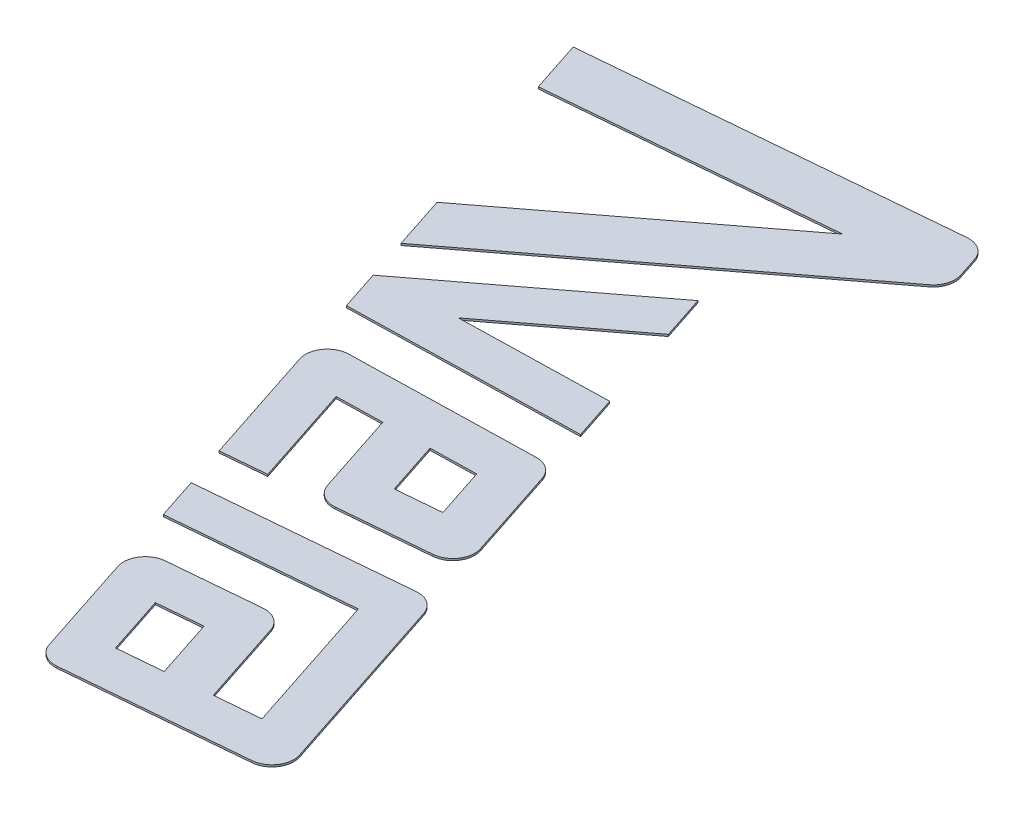
SolidWorks part; units mm, degrees
ref_plane "Front Plane" through (0, 0, 0) normal (0, 0, 1) x (1, 0, 0)
ref_plane "Top Plane" through (0, 0, 0) normal (0, 1, 0) x (1, 0, 0)
ref_plane "Right Plane" through (0, 0, 0) normal (1, 0, 0) x (0, 0, -1)
sketch "Sketch1" plane through (0, 0, 0) normal (0, 1, 0) x (1, 0, 0)
  line L0 (6.2636, 13.3847) -> (6.9802, 11.1991) construction
  line L2 (6.9802, 11.1991) -> (16.6844, 18.5822)
  line L4 (6.9802, 11.1991) -> (7.6656, 9.1086)
  line L5 (19.6969, 9.3941) -> (20.4135, 7.2086) construction
  line L6 (7.6656, 9.1086) -> (19.6969, 9.3941)
  line L10 (7.6656, 9.1086) -> (8.3822, 6.9231) construction
  line L11 (19.5596, 7.1883) -> (9.93, 6.9598)
  line L15 (19.6969, 9.3941) -> (18.9484, 11.677)
  line L20 (11.1641, 11.4923) -> (18.9484, 11.677)
  line L21 (11.1641, 11.4923) -> (17.4428, 16.2692)
  line L26 (11.5324, 4.6972) -> (13.2849, -0.6478)
  line L27 (17.4428, 16.2692) -> (16.6844, 18.5822)
  line L32 (13.0803, 4.7339) -> (11.5324, 4.6972)
  line L39 (5.3404, 16.2005) -> (2.7423, 24.1247) construction
  line L45 (17.2762, 2.0125) -> (16.3584, 4.8117)
  line L46 (13.2849, -0.6478) -> (10.9324, -0.855)
  line L56 (13.0821, -7.4116) -> (20.1616, -6.7881) construction
  line L58 (6.2636, 13.3847) -> (5.3404, 16.2005)
  line L59 (17.4595, 25.4208) -> (5.3404, 16.2005)
  line L60 (13.0821, -7.4116) -> (15.5745, -15.0134) construction
  line L61 (15.5745, -15.0134) -> (27.3591, -13.9756) construction
  line L62 (20.4135, 7.2086) -> (8.3822, 6.9231) construction
  line L64 (20.4135, 7.2086) -> (22.717, 0.1828) construction
  line L65 (8.8645, 5.4519) -> (10.9324, -0.855)
  line L66 (18.7602, 4.8687) -> (16.3584, 4.8117)
  line L68 (20.6796, 6.3969) -> (22.2656, 1.5595)
  line L69 (14.2003, 3.9425) -> (15.3531, 0.4267)
  line L71 (18.7602, 4.8687) -> (19.6287, 2.2197)
  line L72 (19.6287, 2.2197) -> (17.2762, 2.0125)
  line L73 (21.2738, 0.0557) -> (16.5467, -0.3606)
  line L74 (22.717, 0.1828) -> (10.9324, -0.855) construction
  line L75 (18.7602, 4.8687) -> (8.4367, 4.6237) construction
  line L76 (11.6489, -3.0405) -> (12.3655, -5.2261)
  line L77 (19.6287, 2.2197) -> (10.7306, 1.4361) construction
  line L78 (10.9324, -0.855) -> (11.6489, -3.0405) construction
  line L79 (11.6489, -3.0405) -> (22.5243, -2.0828)
  line L80 (12.3655, -5.2261) -> (21.7976, -4.3954)
  line L81 (23.718, -2.8701) -> (26.9077, -12.5989)
  line L82 (21.7976, -4.3954) -> (24.2708, -11.9387)
  line L83 (12.3655, -5.2261) -> (13.0821, -7.4116) construction
  line L84 (20.446, -7.6555) -> (21.9183, -12.1459)
  line L85 (14.5253, -7.2845) -> (19.2524, -6.8682)
  line L86 (13.5335, -8.7884) -> (15.2901, -14.1461)
  line L87 (16.4837, -14.9334) -> (25.9159, -14.1027)
  line L88 (21.2481, -2.7193) -> (25.1736, -14.6922) construction
  line L89 (17.1912, -12.5622) -> (19.5438, -12.355)
  line L90 (23.4336, -2.0027) -> (27.3591, -13.9756) construction
  line L91 (15.3727, -12.7223) -> (27.1574, -11.6845) construction
  line L92 (16.1704, -9.4485) -> (17.1912, -12.5622)
  line L93 (16.1704, -9.4485) -> (18.5229, -9.2414)
  line L95 (16.1704, -9.4485) -> (17.76, -14.2969) construction
  line L96 (18.5449, -9.2394) -> (19.7327, -12.8624) construction
  line L97 (21.9183, -12.1459) -> (24.2708, -11.9387)
  line L98 (1.8466, 26.8566) -> (2.7423, 24.1247)
  line L99 (16.1704, -9.4485) -> (18.5449, -9.2394) construction
  line L100 (18.5229, -9.2414) -> (19.5438, -12.355)
  line L101 (20.1616, -6.7881) -> (21.9183, -12.1459) construction
  line L102 (14.2003, 3.9425) -> (13.9342, 4.7542)
  line L103 (13.0803, 4.7339) -> (13.9342, 4.7542)
  line L104 (15.2901, -14.1461) -> (17.5856, -21.1472) construction
  line L105 (17.4595, 25.4208) -> (2.7423, 24.1247)
  line L106 (22.4342, 26.6593) -> (22.0779, 27.746)
  line L107 (22.0377, 25.3858) -> (6.2636, 13.3847)
  line L108 (17.5856, -21.1472) -> (27.4307, -20.2802) construction
  line L109 (20.8842, 28.5333) -> (1.8466, 26.8566)
  line L110 (21.9183, -12.1459) -> (25.2554, -22.324) construction
  line L111 (17.5856, -21.1472) -> (19.4143, -26.7249) construction
  line L112 (19.4143, -26.7249) -> (29.6028, -25.8276) construction
  arc A0 (14.5253, -7.2845) -> (13.5335, -8.7884) centre (14.6262, -8.4301) ccw
  arc A1 (16.4837, -14.9334) -> (15.2901, -14.1461) centre (16.3829, -13.7878) cw
  arc A2 (22.0377, 25.3858) -> (22.4342, 26.6593) centre (21.3414, 26.301) ccw
  arc A3 (22.0779, 27.746) -> (20.8842, 28.5333) centre (20.9851, 27.3877) ccw
  arc A5 (9.93, 6.9598) -> (8.8645, 5.4519) centre (9.9573, 5.8101) ccw
  arc A6 (19.5596, 7.1883) -> (20.6796, 6.3969) centre (19.5868, 6.0387) cw
  arc A7 (25.9159, -14.1027) -> (26.9077, -12.5989) centre (25.815, -12.9572) ccw
  arc A8 (23.718, -2.8701) -> (22.5243, -2.0828) centre (22.6252, -3.2284) ccw
  arc A9 (16.5467, -0.3606) -> (15.3531, 0.4267) centre (16.4458, 0.785) cw
  arc A10 (21.2738, 0.0557) -> (22.2656, 1.5595) centre (21.1729, 1.2013) ccw
  arc A11 (19.2524, -6.8682) -> (20.446, -7.6555) centre (19.3533, -8.0138) cw
  dimension "D1" = 1.15
  dimension "D2" = 1.15
extrude "Boss-Extrude1" add sketch "Sketch1" along normal blind 0.1
